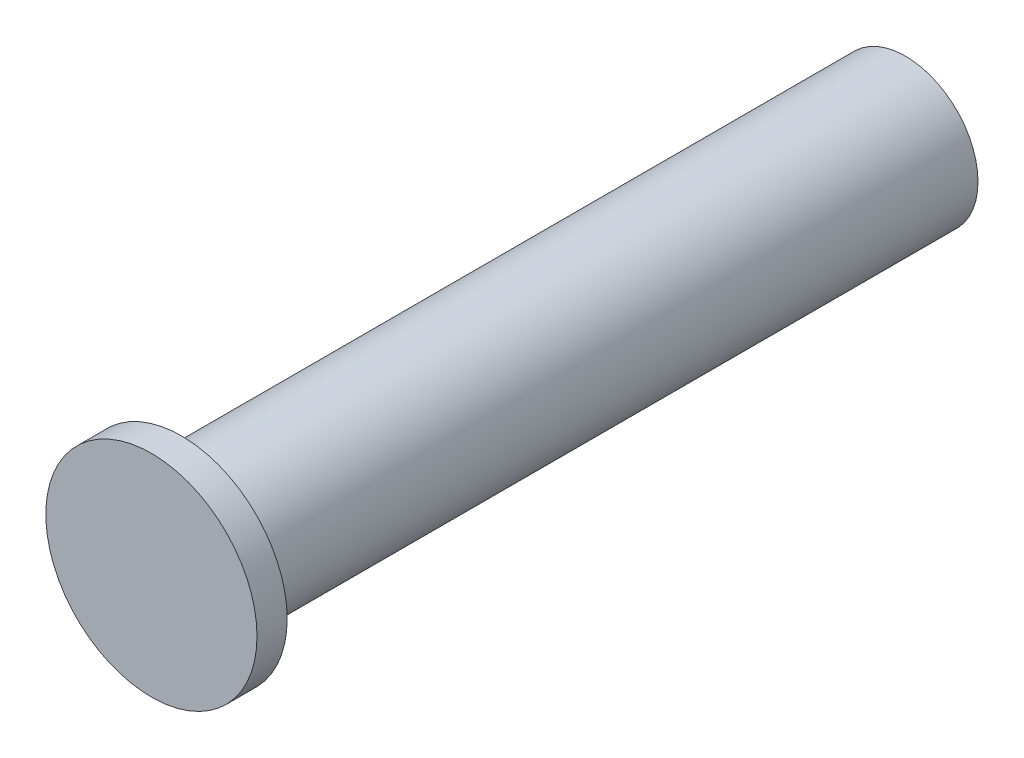
SolidWorks part; units mm, degrees
ref_plane "Front Plane" through (0, 0, 0) normal (0, 0, 1) x (1, 0, 0)
ref_plane "Top Plane" through (0, 0, 0) normal (0, 1, 0) x (1, 0, 0)
ref_plane "Right Plane" through (0, 0, 0) normal (1, 0, 0) x (0, 0, -1)
sketch "Sketch1" plane through (0, 0, 0) normal (0, 0, 1) x (1, 0, 0)
  circle A0 centre (0, 0) radius 4.8
  dimension "D1" = 9.6
extrude "Boss-Extrude1" add sketch "Sketch1" along normal blind 48
sketch "Sketch2" plane through (0, 0, 48) normal (0, 0, 1) x (1, 0, 0)
  circle A0 centre (0, 0) radius 7
  dimension "D1" = 14
extrude "Boss-Extrude2" add sketch "Sketch2" along normal blind 2
